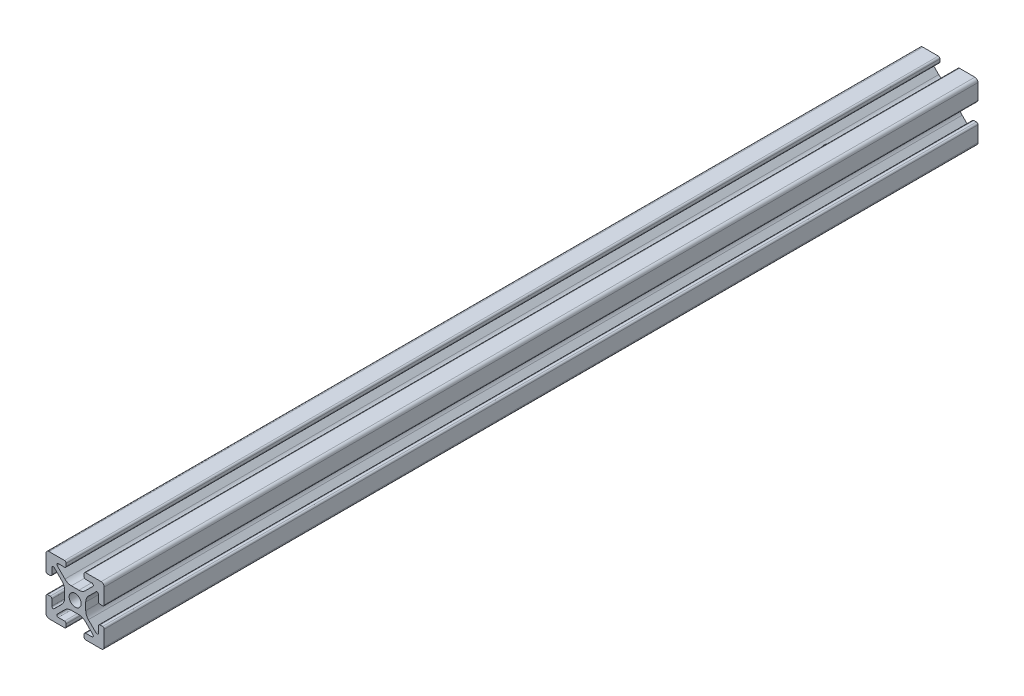
SolidWorks part; units mm, degrees
ref_plane "Front Plane" through (0, 0, 0) normal (0, 0, 1) x (1, 0, 0)
ref_plane "Top Plane" through (0, 0, 0) normal (0, 1, 0) x (1, 0, 0)
ref_plane "Right Plane" through (0, 0, 0) normal (1, 0, 0) x (0, 0, -1)
sketch "Sketch2" plane through (0, 0, 0) normal (0, 0, 1) x (1, 0, 0)
  line L0 (-3.6422, 1.2878) -> (-3.6422, -1.2878)
  line L1 (-1.2878, 3.6422) -> (1.2878, 3.6422)
  line L2 (-9.4433, 3.069) -> (-8.553, 3.069)
  line L3 (0, 0) -> (-15.7854, 0) construction
  line L4 (-3.4964, 4.5571) -> (-6.1213, 7.182)
  line L5 (-3.622, 8) -> (-5.7825, 8)
  line L6 (-3.069, 9.4433) -> (-3.069, 8.553)
  line L7 (-3.622, 10) -> (-8.939, 10)
  line L8 (0, 0) -> (0, 15.0393) construction
  line L9 (10, 3.622) -> (10, 8.939)
  line L10 (8, 3.622) -> (8, 5.7825)
  line L11 (4.5571, 3.4964) -> (7.182, 6.1213)
  line L12 (3.622, 10) -> (8.939, 10)
  line L13 (3.069, 9.4433) -> (3.069, 8.553)
  line L14 (3.622, 8) -> (5.7825, 8)
  line L15 (3.4964, 4.5571) -> (6.1213, 7.182)
  line L16 (9.4433, 3.069) -> (8.553, 3.069)
  line L17 (3.6422, 1.2878) -> (3.6422, -1.2878)
  line L18 (-10, -3.622) -> (-10, -8.939)
  line L19 (-8, -3.622) -> (-8, -5.7825)
  line L20 (-4.5571, -3.4964) -> (-7.182, -6.1213)
  line L21 (9.4433, -3.069) -> (8.553, -3.069)
  line L22 (3.4964, -4.5571) -> (6.1213, -7.182)
  line L23 (3.622, -8) -> (5.7825, -8)
  line L24 (3.069, -9.4433) -> (3.069, -8.553)
  line L25 (3.622, -10) -> (8.939, -10)
  line L26 (4.5571, -3.4964) -> (7.182, -6.1213)
  line L27 (8, -3.622) -> (8, -5.7825)
  line L28 (10, -3.622) -> (10, -8.939)
  line L29 (-3.622, -10) -> (-8.939, -10)
  line L30 (-3.069, -9.4433) -> (-3.069, -8.553)
  line L31 (-3.622, -8) -> (-5.7825, -8)
  line L32 (-3.4964, -4.5571) -> (-6.1213, -7.182)
  line L33 (-9.4433, -3.069) -> (-8.553, -3.069)
  line L34 (-1.2878, -3.6422) -> (1.2878, -3.6422)
  line L48 (-4.5571, 3.4964) -> (-7.182, 6.1213)
  line L49 (-8, 3.622) -> (-8, 5.7825)
  line L52 (-10, 3.622) -> (-10, 8.939)
  arc A0 (-8.553, 3.069) -> (-8, 3.622) centre (-8.553, 3.622) ccw
  arc A1 (-8, 5.7825) -> (-7.182, 6.1213) centre (-7.5208, 5.7825) cw
  arc A2 (-4.5571, 3.4964) -> (-3.6422, 1.2878) centre (-6.7657, 1.2878) cw
  arc A3 (-3.4964, 4.5571) -> (-1.2878, 3.6422) centre (-1.2878, 6.7657) ccw
  arc A4 (-5.7825, 8) -> (-6.1213, 7.182) centre (-5.7825, 7.5208) ccw
  arc A5 (-3.622, 10) -> (-3.069, 9.4433) centre (-3.622, 9.447) cw
  arc A6 (-3.069, 8.553) -> (-3.622, 8) centre (-3.622, 8.553) cw
  arc A7 (8.939, 10) -> (10, 8.939) centre (8.939, 8.939) cw
  arc A8 (10, 3.622) -> (9.4433, 3.069) centre (9.447, 3.622) cw
  arc A9 (3.069, 8.553) -> (3.622, 8) centre (3.622, 8.553) ccw
  arc A10 (3.622, 10) -> (3.069, 9.4433) centre (3.622, 9.447) ccw
  arc A11 (5.7825, 8) -> (6.1213, 7.182) centre (5.7825, 7.5208) cw
  arc A12 (3.4964, 4.5571) -> (1.2878, 3.6422) centre (1.2878, 6.7657) cw
  arc A13 (4.5571, 3.4964) -> (3.6422, 1.2878) centre (6.7657, 1.2878) ccw
  arc A14 (8, 5.7825) -> (7.182, 6.1213) centre (7.5208, 5.7825) ccw
  arc A15 (8.553, 3.069) -> (8, 3.622) centre (8.553, 3.622) cw
  arc A16 (-8.939, -10) -> (-10, -8.939) centre (-8.939, -8.939) cw
  arc A17 (-10, -3.622) -> (-9.4433, -3.069) centre (-9.447, -3.622) cw
  arc A18 (8.553, -3.069) -> (8, -3.622) centre (8.553, -3.622) ccw
  arc A19 (8, -5.7825) -> (7.182, -6.1213) centre (7.5208, -5.7825) cw
  arc A20 (4.5571, -3.4964) -> (3.6422, -1.2878) centre (6.7657, -1.2878) cw
  arc A21 (3.4964, -4.5571) -> (1.2878, -3.6422) centre (1.2878, -6.7657) ccw
  arc A22 (5.7825, -8) -> (6.1213, -7.182) centre (5.7825, -7.5208) ccw
  arc A23 (3.622, -10) -> (3.069, -9.4433) centre (3.622, -9.447) cw
  arc A24 (3.069, -8.553) -> (3.622, -8) centre (3.622, -8.553) cw
  arc A25 (10, -3.622) -> (9.4433, -3.069) centre (9.447, -3.622) ccw
  arc A26 (8.939, -10) -> (10, -8.939) centre (8.939, -8.939) ccw
  arc A27 (-3.069, -8.553) -> (-3.622, -8) centre (-3.622, -8.553) ccw
  arc A28 (-3.622, -10) -> (-3.069, -9.4433) centre (-3.622, -9.447) ccw
  arc A29 (-5.7825, -8) -> (-6.1213, -7.182) centre (-5.7825, -7.5208) cw
  arc A30 (-3.4964, -4.5571) -> (-1.2878, -3.6422) centre (-1.2878, -6.7657) cw
  arc A31 (-4.5571, -3.4964) -> (-3.6422, -1.2878) centre (-6.7657, -1.2878) ccw
  arc A32 (-8, -5.7825) -> (-7.182, -6.1213) centre (-7.5208, -5.7825) ccw
  arc A33 (-8.553, -3.069) -> (-8, -3.622) centre (-8.553, -3.622) cw
  arc A51 (-10, 3.622) -> (-9.4433, 3.069) centre (-9.447, 3.622) ccw
  arc A56 (-8.939, 10) -> (-10, 8.939) centre (-8.939, 8.939) ccw
  circle A57 centre (0, 0) radius 2.05
  point P1 (-3.6422, 0)
  point P46 (0, 0)
  point P48 (0, 0)
  point P53 (0, 3.6422)
  point P60 (0, 0)
  point P61 (0, 0)
  point P62 (0, 0)
  point P74 (0, 0)
  point P85 (0, 0)
  point P87 (0, 0)
  point P99 (0, 0)
  point P101 (0, 0)
  point P102 (0, 0)
  point P116 (0, -3.6422)
  point P117 (3.6422, 0)
  point P123 (0, 0)
  point P125 (0, 0)
  point P127 (0, 0)
  point P139 (0, 0)
  point P140 (0, 0)
  point P141 (0, 0)
  point P142 (0, 0)
  point P179 (0, 0)
  point P192 (0, 0)
  point P193 (0, 0)
  dimension "D1" = 0.553
  dimension "D3" = 3.1235
  dimension "D4" = 0.553
  dimension "D2" = 0.4792
  dimension "D5" = 1.061
  dimension "D6" = 2.05
extrude "Boss-Extrude1" add sketch "Sketch2" against normal blind 300
sketch "Sketch4" plane through (0, -10, 0) normal (0, -1, 0) x (1, 0, 0)
  line L0 (-1.2878, -300) -> (1.2878, -300) construction
  line L1 (10, -300) -> (10, 0) construction
  circle A0 centre (0, -260) radius 2.8
  point P4 (0, -300)
  dimension "D2" = 5.6
  dimension "D1" = 40
  dimension "D3" = 10
extrude "Cut-Extrude1" cut sketch "Sketch4" against normal blind 43
